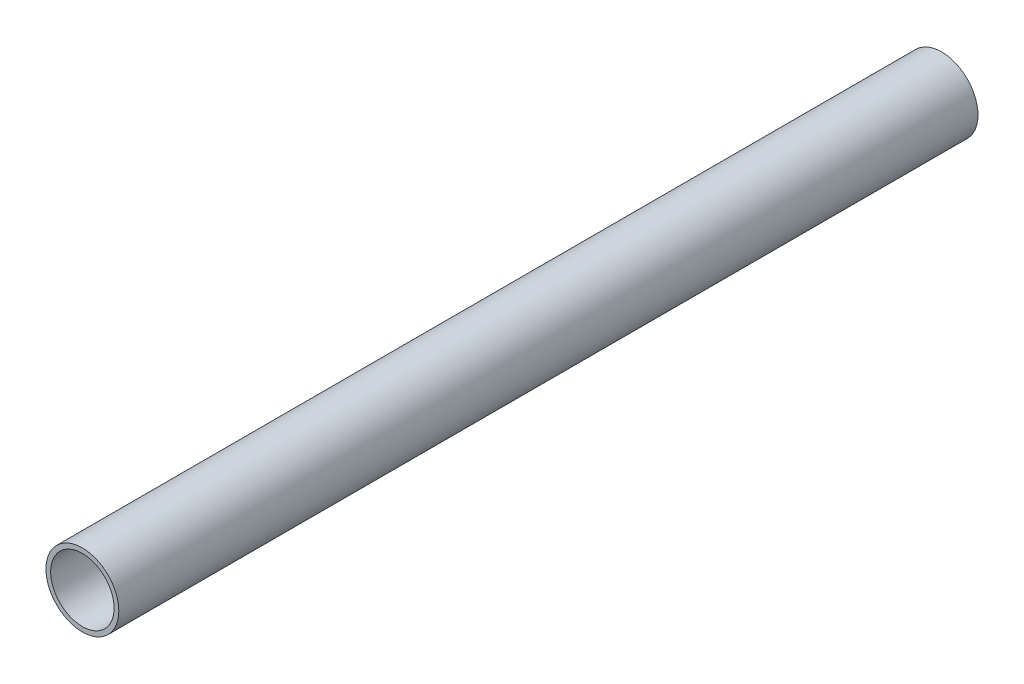
SolidWorks part; units mm, degrees
ref_plane "Front Plane" through (0, 0, 0) normal (0, 0, 1) x (1, 0, 0)
ref_plane "Top Plane" through (0, 0, 0) normal (0, 1, 0) x (1, 0, 0)
ref_plane "Right Plane" through (0, 0, 0) normal (1, 0, 0) x (0, 0, -1)
sketch "Sketch1" plane through (0, 0, 0) normal (0, 0, 1) x (1, 0, 0)
  circle A0 centre (0, 0) radius 30.1625
  circle A1 centre (0, 0) radius 26.2509
  dimension "D1" = 60.325
  dimension "D2" = 3.9116
extrude "Boss-Extrude1" add sketch "Sketch1" along normal blind 711.2
